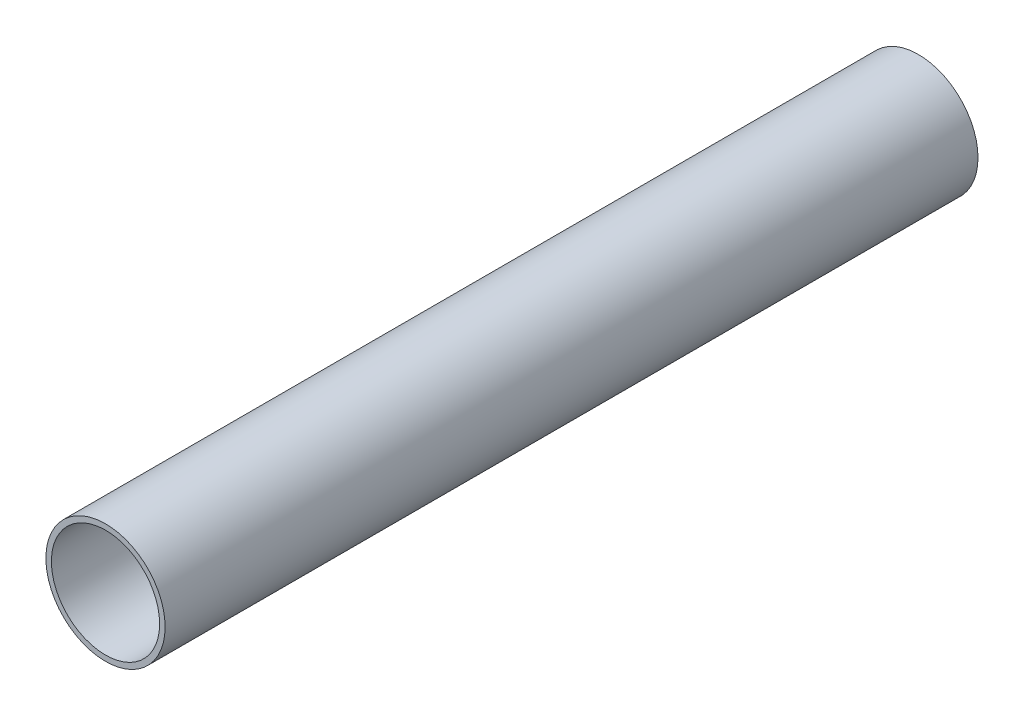
SolidWorks part; units mm, degrees
ref_plane "Front Plane" through (0, 0, 0) normal (0, 0, 1) x (1, 0, 0)
ref_plane "Top Plane" through (0, 0, 0) normal (0, 1, 0) x (1, 0, 0)
ref_plane "Right Plane" through (0, 0, 0) normal (1, 0, 0) x (0, 0, -1)
ref_plane "Plane1"
sketch "Sketch1" plane through (0, 0, 0) normal (0, 0, 1) x (1, 0, 0)
  circle A0 centre (0.1401, 0) radius 55
  circle A1 centre (0.1401, 0) radius 49.92
  dimension "D1" = 110
extrude "Extrusion1" add sketch "Sketch1" along normal blind 750 contours A0 A1
